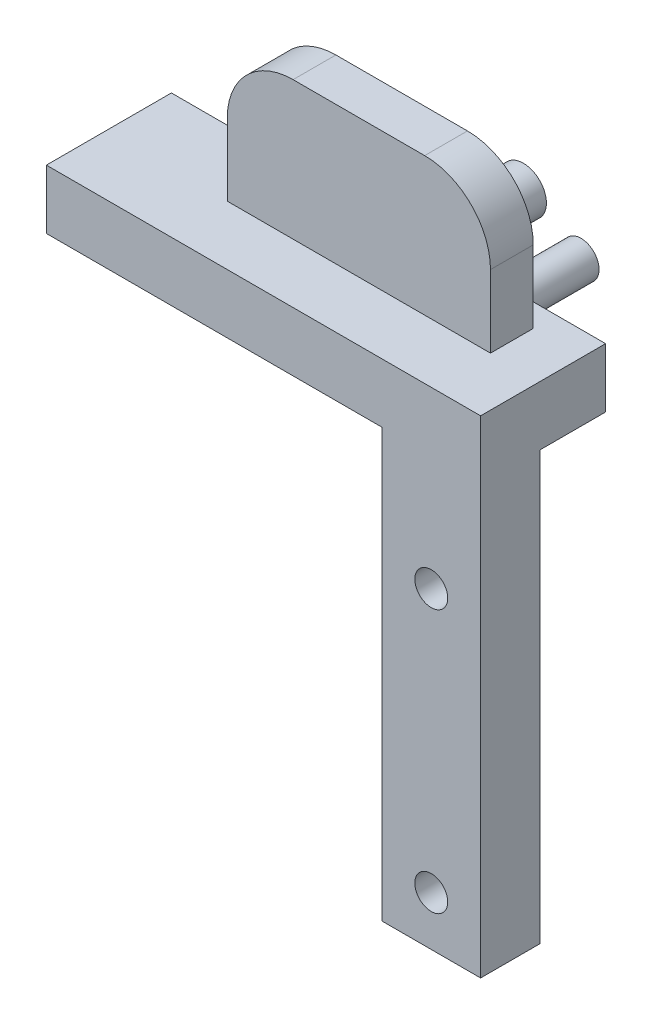
SolidWorks part; units mm, degrees
ref_plane "Front Plane" through (0, 0, 0) normal (0, 0, 1) x (1, 0, 0)
ref_plane "Top Plane" through (0, 0, 0) normal (0, 1, 0) x (1, 0, 0)
ref_plane "Right Plane" through (0, 0, 0) normal (1, 0, 0) x (0, 0, -1)
sketch "Sketch1" plane through (0, 0, 0) normal (0, 1, 0) x (1, 0, 0)
  line L1 (-11, 8.5) -> (55, 8.5)
  line L2 (-11, 8.5) -> (-11, 27.5)
  line L3 (-11, 27.5) -> (55, 27.5)
  line L4 (55, 8.5) -> (55, 27.5)
  point P5 (0, 0)
  point P6 (0, 0)
  point P29 (0, 0)
  dimension "D1" = 66
  dimension "D2" = 19
extrude "Boss-Extrude2" add sketch "Sketch1" along normal blind 8 and the other way blind 1
sketch "Sketch3" plane through (0, 0, -27.5) normal (0, 0, -1) x (-1, 0, 0)
  line L1 (-55, -1) -> (-37.5, -1) construction
  line L2 (-55, -1) -> (-55, 3.5) construction
  line L3 (-55, 3.5) -> (-37.5, 3.5) construction
  line L4 (-37.5, -1) -> (-37.5, 3.5) construction
  circle A0 centre (-37.5, 3.5) radius 2.75
  circle A1 centre (-17.5, 3.5) radius 2.75
  dimension "D3" = 5.5
  dimension "D1" = 4.5
  dimension "D2" = 17.5
  dimension "D4" = 2
extrude "Boss-Extrude3" add sketch "Sketch3" along normal blind 13.75
sketch "Sketch4" plane through (0, 8, 0) normal (0, 1, 0) x (1, 0, 0)
  line L2 (27.5, 27.5) -> (27.5, 0) construction
  line L4 (55, 24) -> (55, 17.5)
  line L9 (27.5, 27.5) -> (27.5, 24)
  line L11 (27.5, 24) -> (32, 24)
  line L12 (27.5, 24) -> (27.5, 17.5)
  line L13 (27.5, 17.5) -> (32, 17.5)
  line L14 (32, 24) -> (32, 17.5)
  line L15 (27.5, 24) -> (23, 24)
  line L16 (27.5, 24) -> (27.5, 17.5)
  line L17 (27.5, 17.5) -> (23, 17.5)
  line L18 (23, 24) -> (23, 17.5)
  dimension "D4" = 3.5
  dimension "D5" = 4.5
  dimension "D6" = 6.5
  dimension "D7" = 4.5
extrude "Boss-Extrude4" add sketch "Sketch4" along normal blind 15 contours L15 L18 L17 L12 | L14 L11 L12 L13
sketch "Sketch5" plane through (0, 0, -24) normal (0, 0, -1) x (-1, 0, 0)
  line L0 (-27.5, 8) -> (-27.5, 16)
  line L1 (-32, 8) -> (-23, 8) construction
  circle A0 centre (-27.5, 16) radius 3.5
  circle A1 centre (-25.7747, 12.9548) radius 0.161
extrude "Boss-Extrude5" add sketch "Sketch5" along normal blind 8.5
sketch "Sketch6" plane through (0, 0, -32.5) normal (0, 0, -1) x (-1, 0, 0)
  line L0 (-30.9402, 15.3557) -> (-30.9492, 15.4061)
  arc A0 (-25.6364, 13.0374) -> (-25.9166, 12.8787) centre (-27.5, 16) ccw construction
sketch "Sketch8" plane through (0, 23, 0) normal (0, 1, 0) x (1, 0, 0)
  line L1 (32, 24) -> (23, 24)
  line L2 (32, 24) -> (32, 17.5)
  line L3 (32, 17.5) -> (23, 17.5)
  line L4 (23, 24) -> (23, 17.5)
extrude "Boss-Extrude6" add sketch "Sketch8" along normal blind 6
sketch "Sketch9" plane through (0, 8, 0) normal (0, 1, 0) x (1, 0, 0)
  line L0 (27.5, 17.5) -> (47.5, 17.5)
  line L1 (32, 17.5) -> (23, 17.5) construction
  line L3 (47.5, 17.5) -> (7.5, 17.5)
  line L4 (47.5, 17.5) -> (47.5, 24)
  line L5 (47.5, 24) -> (7.5, 24)
  line L6 (7.5, 17.5) -> (7.5, 24)
  line M12 (23, 17.5) -> (23, 24)
  line M14 (32, 24) -> (32, 17.5)
  dimension "D1" = 20
  dimension "D2" = 6.5
  dimension "D3" = 40
extrude "Boss-Extrude7" add sketch "Sketch9" along normal blind 21 contours L6 L3 L5 M12 | L4 L5 L0 M14
sketch "Sketch10" plane through (0, 0, -24) normal (0, 0, -1) x (-1, 0, 0)
  line L0 (-27.5, 17) -> (-7.5, 17)
  line L2 (-7.5, 17) -> (-47.5, 17)
  line L4 (-17.5, 3.5) -> (-17.5, 17)
  line L5 (-37.5, 3.5) -> (-37.5, 17)
  circle A0 centre (-17.5, 17) radius 3.5
  circle A1 centre (-37.5, 17) radius 3.5
  dimension "D1" = 7
  dimension "D2" = 7
  dimension "D3" = 13.5
extrude "Boss-Extrude8" add sketch "Sketch10" along normal blind 8.5 contours L2 A0 | L2 A0 L4 | L2 A1 | L2 A1 L5 | L5 A1 L2
sketch "Sketch12" plane through (0, 0, -32.5) normal (0, 0, -1) x (-1, 0, 0)
  circle A0 centre (-27.5, 16) radius 3.5
extrude "Cut-Extrude2" cut sketch "Sketch12" against normal blind 8.5
fillet "Fillet1" radius 10 2 edges at (47.5, 29, -20.75) (7.5, 29, -20.75)
sketch "Sketch14" plane through (0, -1, 0) normal (0, -1, 0) x (1, 0, 0)
  line L0 (55, -27.5) -> (-22, -27.5) construction
  line L1 (55, -17.5) -> (40, -17.5)
  line L2 (55, -17.5) -> (55, -8.5)
  line L3 (55, -8.5) -> (40, -8.5)
  line L4 (40, -17.5) -> (40, -8.5)
  point P4 (0, 0)
  point P5 (0, 0)
  point P6 (0, 0)
  point P7 (0, 0)
  dimension "D1" = 10
  dimension "D2" = 9
  dimension "D3" = 15
extrude "Boss-Extrude10" add sketch "Sketch14" along normal blind 65
sketch "Sketch15" plane through (0, 0, -17.5) normal (0, 0, -1) x (-1, 0, 0)
  line L0 (-55, -66) -> (-55, -1) construction
  line L1 (-40, -66) -> (-55, -66) construction
  circle A0 centre (-47.5, -58.5) radius 2.5
  circle A1 centre (-47.5, -18.5) radius 2.5
  dimension "D1" = 5
  dimension "D2" = 7.5
  dimension "D3" = 7.5
  dimension "D4" = 5
  dimension "D5" = 47.5
  dimension "D6" = 7.5
extrude "Cut-Extrude3" cut sketch "Sketch15" against normal up to next
